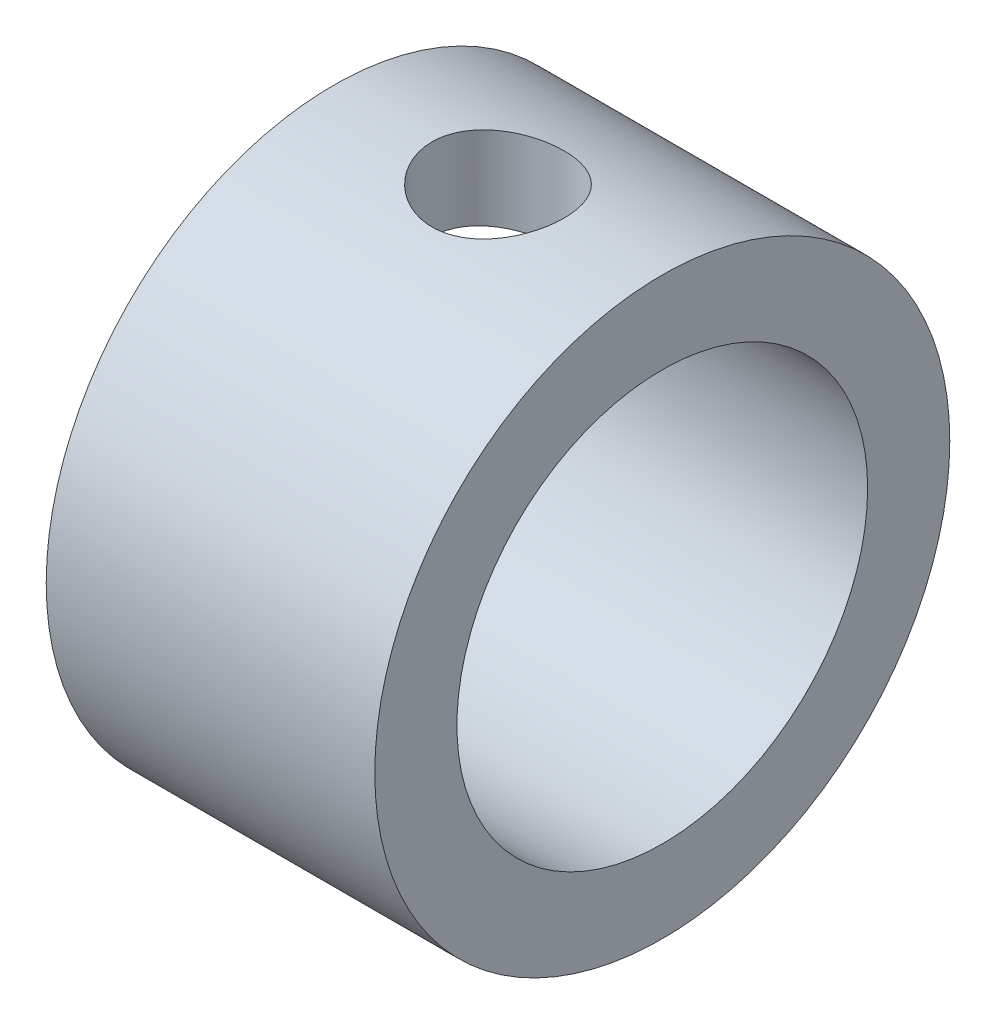
SolidWorks part; units mm, degrees
ref_plane "Front Plane" through (0, 0, 0) normal (0, 0, 1) x (1, 0, 0)
ref_plane "Top Plane" through (0, 0, 0) normal (0, 1, 0) x (1, 0, 0)
ref_plane "Right Plane" through (0, 0, 0) normal (1, 0, 0) x (0, 0, -1)
sketch "Sketch1" plane through (0, 0, 0) normal (1, 0, 0) x (0, 0, -1)
  circle A0 centre (0, 0) radius 7.9375
  circle A1 centre (0, 0) radius 11.1125
  dimension "D1" = 15.875
  dimension "D2" = 22.225
extrude "Boss-Extrude1" add sketch "Sketch1" along normal mid plane 12.7
sketch "Sketch3" plane through (0, 0, 0) normal (0, 1, 0) x (1, 0, 0)
  circle A0 centre (0, 0) radius 2.5527
  dimension "D1" = 5.1054
extrude "Cut-Extrude2" cut sketch "Sketch3" along normal through all
